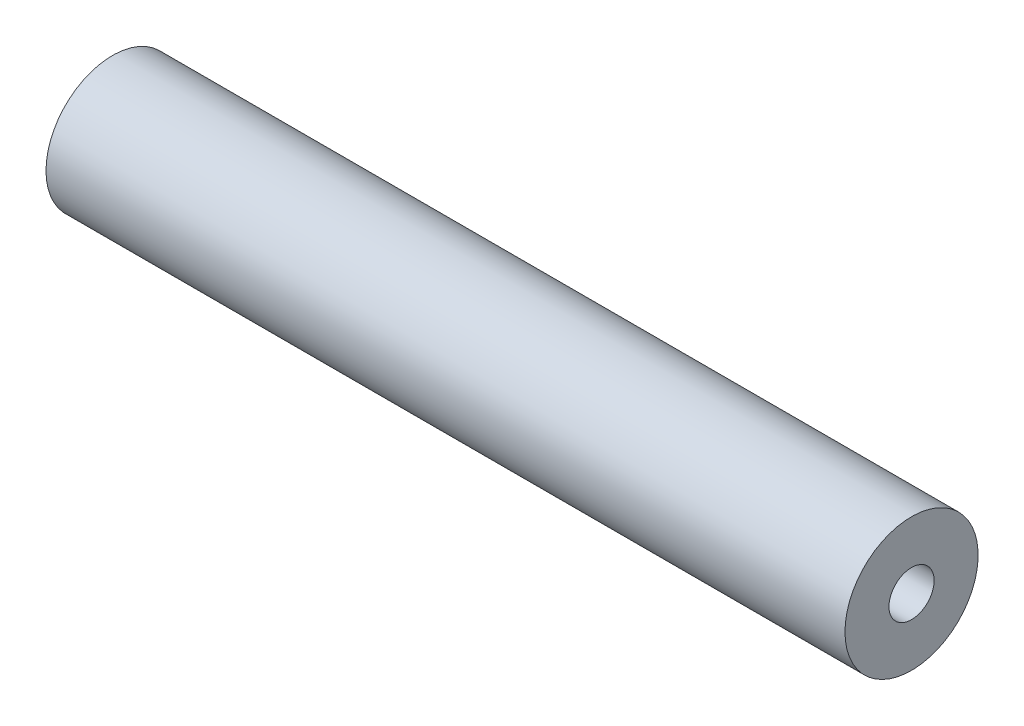
SolidWorks part; units mm, degrees
ref_plane "Front Plane" through (0, 0, 0) normal (0, 0, 1) x (1, 0, 0)
ref_plane "Top Plane" through (0, 0, 0) normal (0, 1, 0) x (1, 0, 0)
ref_plane "Right Plane" through (0, 0, 0) normal (1, 0, 0) x (0, 0, -1)
sketch "Sketch1" plane through (0, 0, 0) normal (1, 0, 0) x (0, 0, -1)
  circle A0 centre (0, 0) radius 6.35
  circle A1 centre (0, 0) radius 2.1526
  dimension "D1" = 12.7
  dimension "D2" = 4.3053
extrude "Boss-Extrude1" add sketch "Sketch1" along normal blind 76.2
